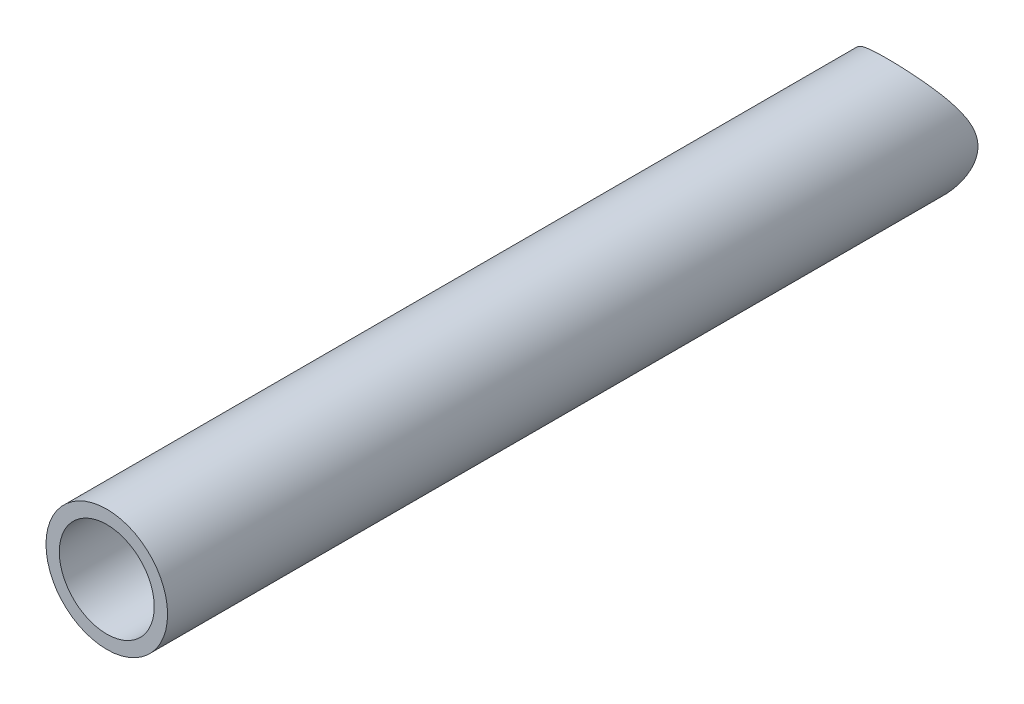
SolidWorks part; units mm, degrees
ref_plane "Front Plane" through (0, 0, 0) normal (0, 0, 1) x (1, 0, 0)
ref_plane "Top Plane" through (0, 0, 0) normal (0, 1, 0) x (1, 0, 0)
ref_plane "Right Plane" through (0, 0, 0) normal (1, 0, 0) x (0, 0, -1)
sketch "Sketch1" plane through (0, 0, 0) normal (0, 0, 1) x (1, 0, 0)
  circle A0 centre (0, 0) radius 13.335
  circle A1 centre (0, 0) radius 10.414
  dimension "D1" = 26.67
  dimension "D2" = 20.828
extrude "Boss-Extrude1" add sketch "Sketch1" along normal blind 177.8
sketch "Sketch2" plane through (0, 0, 0) normal (0, 1, 0) x (1, 0, 0)
  line L0 (13.335, 0) -> (-13.335, 0) construction
  line L1 (-13.335, 0) -> (13.335, 0)
  arc A0 (-13.335, 0) -> (13.335, 0) centre (0, 10.1592) ccw
  dimension "D1" = 16.764
extrude "Cut-Extrude1" cut sketch "Sketch2" against normal through all both and the other way through all
